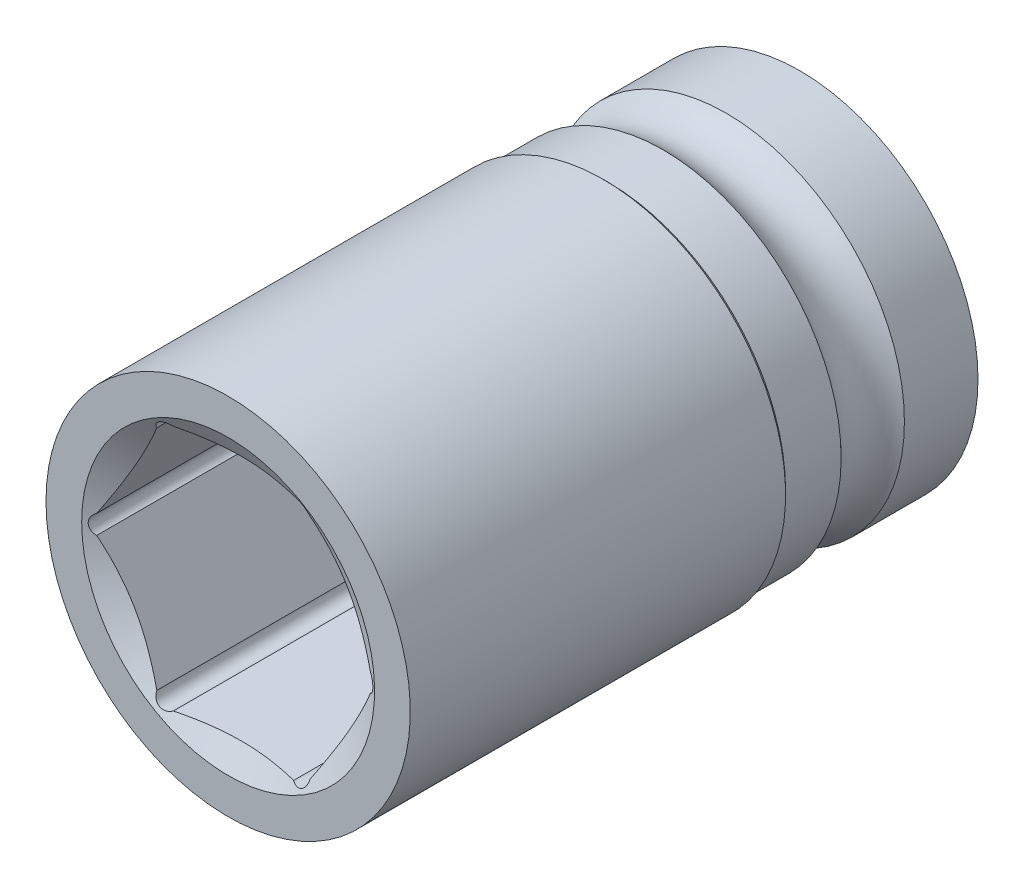
SolidWorks part; units mm, degrees
material "Cast Alloy Steel"
ref_plane "Front Plane" through (0, 0, 0) normal (0, 0, 1) x (1, 0, 0)
ref_plane "Top Plane" through (0, 0, 0) normal (0, 1, 0) x (1, 0, 0)
ref_plane "Right Plane" through (0, 0, 0) normal (1, 0, 0) x (0, 0, -1)
sketch "Sketch1" plane through (0, 0, 0) normal (1, 0, 0) x (0, 0, -1)
  line L0 (0, 24.75) -> (0, 19.9)
  line L1 (0, 24.75) -> (51, 24.75)
  line L2 (51, 24.75) -> (51.55, 24.2)
  line L3 (51.55, 24.2) -> (59.1, 24.2)
  line L4 (67.7, 24.2) -> (77.7, 24.2)
  line L5 (77.7, 24.2) -> (77.7, 19)
  line L6 (66.7303, 0) -> (11.4893, 0)
  line L7 (0, 0) -> (-20.5315, 0) construction
  line L8 (77.7, 19) -> (66.7303, 0)
  line L9 (63.4, 22.275) -> (63.4, 0) construction
  line L10 (0, 19.9) -> (11.4893, 0)
  arc A0 (59.1, 24.2) -> (67.7, 24.2) centre (63.4, 28.0401) ccw
  dimension "D2" = 48.4
  dimension "D3" = 49.5
  dimension "D4" = 51
  dimension "D5" = 38
  dimension "D6" = 45
  dimension "D7" = 8.6
  dimension "D8" = 30
  dimension "D9" = 10
  dimension "D10" = 44.55
  dimension "D11" = 30
  dimension "D12" = 39.8
  dimension "D13" = 77.7
revolve "Revolve1" add sketch "Sketch1" angle 360 about L7
sketch "Sketch2" plane through (0, 0, 0) normal (0, 0, 1) x (1, 0, 0)
  line L0 (-10.4206, 15.451) -> (-18.5912, 1.299)
  line L1 (-8.1706, 16.75) -> (8.1706, 16.75)
  line L2 (0, 0) -> (-19.3412, 0) construction
  line L3 (-8.1706, -16.75) -> (8.1706, -16.75)
  line L4 (-9.6706, 16.75) -> (0, 0) construction
  line L5 (-10.4206, -15.451) -> (-18.5912, -1.299)
  line L6 (0, 0) -> (9.6706, 16.75) construction
  line L7 (18.5912, 1.299) -> (10.4206, 15.451)
  line L8 (18.5912, -1.299) -> (10.4206, -15.451)
  arc A0 (-8.1706, 16.75) -> (-10.4206, 15.451) centre (-8.9206, 15.451) ccw
  arc A1 (10.4206, 15.451) -> (8.1706, 16.75) centre (8.9206, 15.451) ccw
  arc A2 (10.4206, -15.451) -> (8.1706, -16.75) centre (8.9206, -15.451) cw
  arc A3 (-18.5912, 1.299) -> (-18.5912, -1.299) centre (-17.8412, 0) ccw
  arc A4 (-8.1706, -16.75) -> (-10.4206, -15.451) centre (-8.9206, -15.451) cw
  arc A5 (18.5912, -1.299) -> (18.5912, 1.299) centre (17.8412, 0) ccw
  point P1 (0, 0)
  dimension "D2" = 1.5
  dimension "D1" = 33.5
extrude "Cut-Extrude1" cut sketch "Sketch2" against normal blind 33.1
sketch "Sketch3" plane through (0, 0, -33.1) normal (0, 0, 1) x (1, 0, 0)
  circle A0 centre (0, 0) radius 10
  dimension "D1" = 20
extrude "Cut-Extrude2" cut sketch "Sketch3" against normal blind 30
sketch "Sketch4" plane through (0, 0, -77.7) normal (0, 0, -1) x (-1, 0, 0)
  line L0 (-12.85, -9.668) -> (-12.85, 9.668)
  line L1 (-9.668, -12.85) -> (9.668, -12.85)
  line L2 (-9.668, 12.85) -> (9.668, 12.85)
  line L3 (12.85, -9.668) -> (12.85, 9.668)
  line L4 (-12.85, -12.85) -> (12.85, 12.85) construction
  line L5 (-12.85, 12.85) -> (12.85, -12.85) construction
  arc A0 (-12.85, 9.668) -> (-9.668, 12.85) centre (-11.259, 11.259) cw
  arc A1 (9.668, 12.85) -> (12.85, 9.668) centre (11.259, 11.259) cw
  arc A2 (9.668, -12.85) -> (12.85, -9.668) centre (11.259, -11.259) ccw
  arc A3 (-12.85, -9.668) -> (-9.668, -12.85) centre (-11.259, -11.259) ccw
  point P1 (0, 0)
  dimension "D1" = 2.25
  dimension "D2" = 25.7
extrude "Cut-Extrude3" cut sketch "Sketch4" against normal blind 31.3
sketch "Sketch5" plane through (0, 0, -33.1) normal (0, 0, 1) x (1, 0, 0)
  circle A0 centre (0, 0) radius 15
  dimension "D1" = 30
extrude "Cut-Extrude4" cut sketch "Sketch5" against normal blind 8
